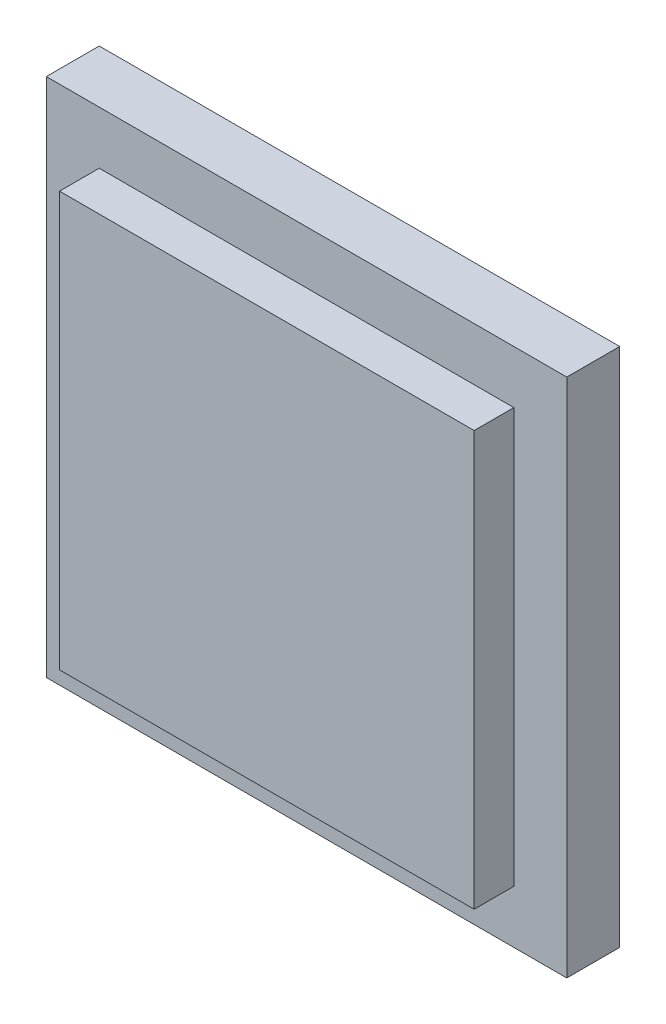
SolidWorks part; units mm, degrees
ref_plane "Plan de face" through (0, 0, 0) normal (0, 0, 1) x (1, 0, 0)
ref_plane "Plan de dessus" through (0, 0, 0) normal (0, 1, 0) x (1, 0, 0)
ref_plane "Plan de droite" through (0, 0, 0) normal (1, 0, 0) x (0, 0, -1)
sketch "Esquisse1" plane through (0, 0, 0) normal (0, 0, 1) x (1, 0, 0)
  line L1 (-29.5, -29.5) -> (29.5, -29.5)
  line L2 (-29.5, -29.5) -> (-29.5, 29.5)
  line L3 (-29.5, 29.5) -> (29.5, 29.5)
  line L4 (29.5, -29.5) -> (29.5, 29.5)
  point P4 (0, 29.5)
  point P6 (29.5, 0)
  dimension "D1" = 59
extrude "Boss.-Extru.1" add sketch "Esquisse1" along normal blind 6
sketch "Esquisse2" plane through (0, 0, 6) normal (0, 0, 1) x (1, 0, 0)
  line L1 (-23.5, -23.5) -> (23.5, -23.5)
  line L2 (-23.5, -23.5) -> (-23.5, 23.5)
  line L3 (-23.5, 23.5) -> (23.5, 23.5)
  line L4 (23.5, -23.5) -> (23.5, 23.5)
  point P4 (0, 23.5)
  point P6 (23.5, 0)
  dimension "D1" = 47
extrude "Boss.-Extru.2" add sketch "Esquisse2" along normal blind 4.5
